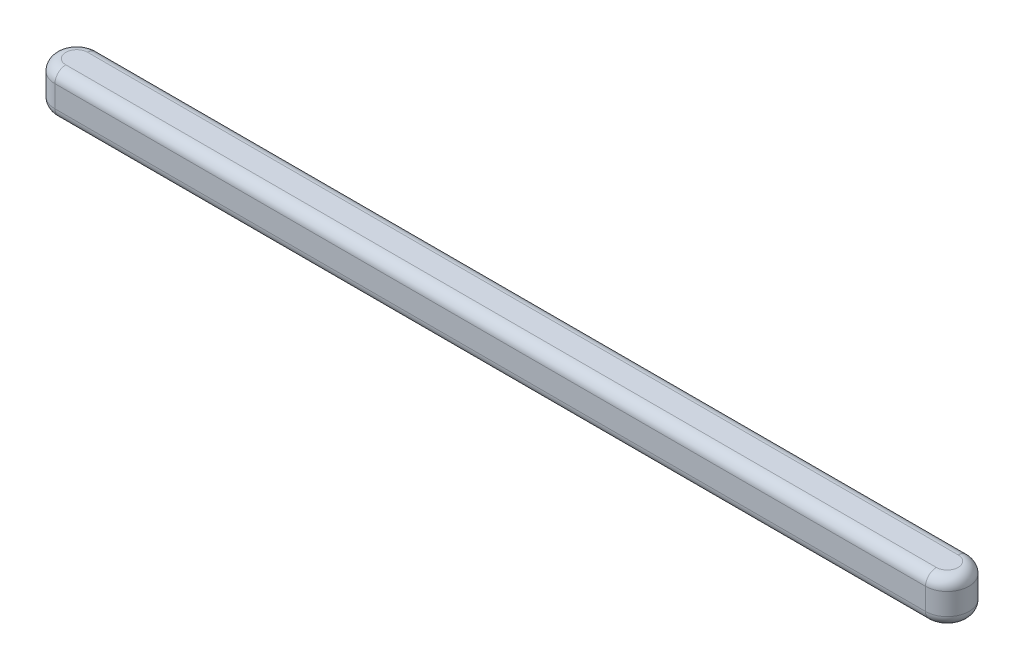
SolidWorks part; units mm, degrees
ref_plane "Front Plane" through (0, 0, 0) normal (0, 0, 1) x (1, 0, 0)
ref_plane "Top Plane" through (0, 0, 0) normal (0, 1, 0) x (1, 0, 0)
ref_plane "Right Plane" through (0, 0, 0) normal (1, 0, 0) x (0, 0, -1)
sketch "Sketch1" plane through (0, 0, 0) normal (0, 1, 0) x (1, 0, 0)
  line L0 (0, 0) -> (200, 0) construction
  line L1 (0, 5) -> (200, 5)
  line L2 (0, -5) -> (200, -5)
  arc A0 (0, 5) -> (0, -5) centre (0, 0) ccw
  arc A1 (200, -5) -> (200, 5) centre (200, 0) ccw
  point P3 (100, 0)
  dimension "D1" = 5
  dimension "D2" = 200
extrude "Boss-Extrude1" add sketch "Sketch1" along normal blind 10
fillet "Fillet1" radius 2.5 8 edges at (100, 0, 5) (205, 0, 0) (100, 0, -5) (-5, 0, 0) (100, 10, -5) (205, 10, 0) (100, 10, 5) (-5, 10, 0)
